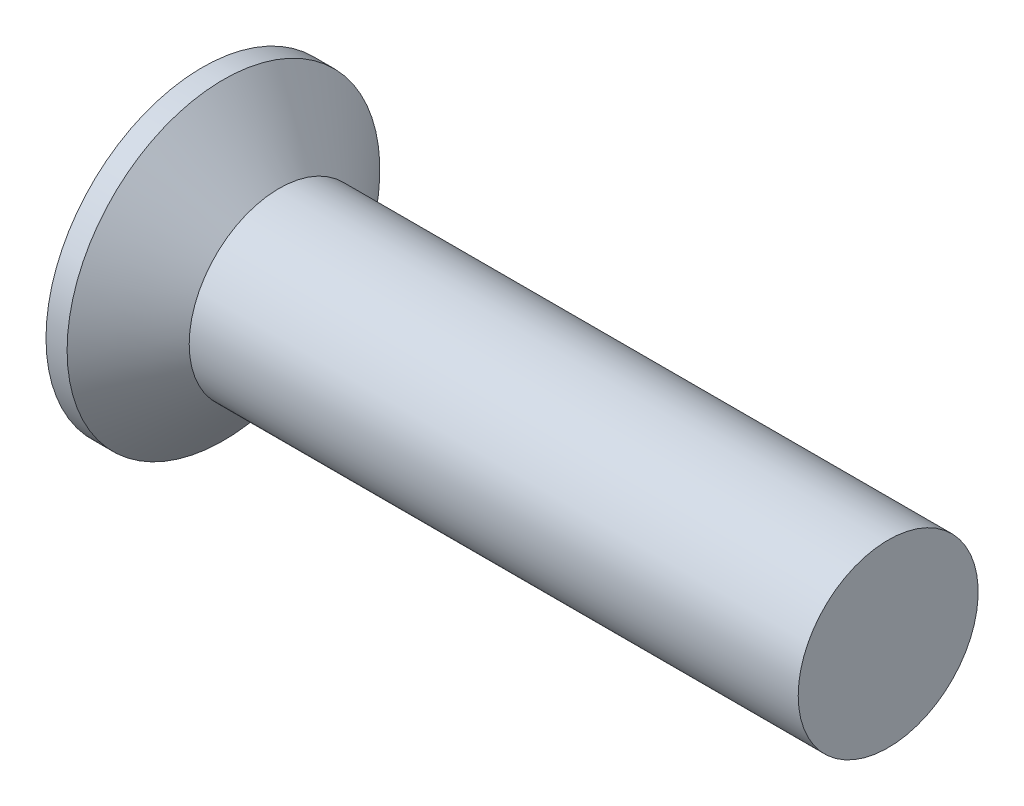
SolidWorks part; units mm, degrees
revolve "Base-Revolve" add sketch "BodySke" angle 360 about L5
sketch "BodySke" plane through (0, 0, 0) normal (0, 0, 1) x (1, 0, 0)
  line L0 (0, 0) -> (0, 3.6195)
  line L1 (0, 3.6195) -> (0.4886, 3.6195)
  line L2 (1.778, 2.0828) -> (15.875, 2.0828)
  line L3 (15.875, 2.0828) -> (15.875, 0)
  line L4 (15.875, 0) -> (0, 0)
  line L5 (-6.35, 0) -> (82.55, 0) construction
  line L6 (1.778, -2.0828) -> (15.875, -2.0828) construction
  line L7 (0.4886, -3.6195) -> (1.778, -2.0828) construction
  line L8 (0.4886, 3.6195) -> (1.778, 2.0828)
  line L9 (0, -3.6195) -> (0.4886, -3.6195) construction
  line L10 (2.5705, 3.6703) -> (2.5705, -5.8547) construction
  line L11 (0, 6.35) -> (0, -3.175) construction
  dimension "Diameter" = 4.1656
  dimension "Length" = 15.875
  dimension "Head_ht" = 1.778
  dimension "Head_dia" = 7.239
  dimension "Head_ang" = 100
  dimension "D6" = 0.4886
  dimension "Advance" = 0.7925
  dimension "Thread_nom" = 15.875
cosmetic thread "ThreadCosmetic" [suppressed] parameters "Thread_length"=13.3045, "Thread_minor"=3.2207
extrude "Slot" [suppressed] cut sketch "Sketch2" against normal blind 0.9144
sketch "Sketch2" plane through (0, 0, 0) normal (-1, 0, 0) x (0, 0, 1)
  line L0 (-3.6195, -0.6858) -> (3.6195, -0.6858)
  line L1 (-3.6195, -0.6858) -> (-3.6195, 0.6858)
  line L2 (3.6195, 0.6858) -> (-3.6195, 0.6858)
  line L3 (3.6195, 0.6858) -> (3.6195, -0.6858)
  dimension "Slot_width" = 1.3716
  dimension "D1" = 0.6858
  dimension "D2" = 7.239
  dimension "D3" = 3.6195
ref_plane "Plane1" through (0, 0, 0) normal (0, 0, 1) x (1, 0, 0)
ref_plane "Plane2" through (0, 0, 0) normal (0, 1, 0) x (1, 0, 0)
ref_plane "Plane3" through (0, 0, 0) normal (1, 0, 0) x (0, 0, -1)
sketch "Sketch3" plane through (0, 0, 0) normal (-1, 0, 0) x (0, 0, 1)
  line L0 (-0.4699, 2.4257) -> (0.4699, 2.4257)
  line L1 (0.4699, 2.4257) -> (0.4699, -2.4257)
  line L2 (0.4699, -2.4257) -> (-0.4699, -2.4257)
  line L3 (-0.4699, -2.4257) -> (-0.4699, 2.4257)
  dimension "Cross_dia" = 4.8514
  dimension "Cross_width" = 0.9398
  dimension "D1" = 2.4257
  dimension "D2" = 0.4699
ref_plane "Plane4" through (3.1496, 0, 0) normal (-1, 0, 0) x (0, 0, 1)
sketch "Sketch4" plane through (3.1496, 0, 0) normal (-1, 0, 0) x (0, 0, 1)
  line L0 (-0.2349, 0.2349) -> (0.2349, 0.235)
  line L3 (0.2349, 0.235) -> (0.235, -0.235)
  line L4 (0.235, -0.235) -> (-0.2349, -0.235)
  line L5 (-0.2349, -0.235) -> (-0.2349, 0.2349)
  dimension "D2" = 0.4699
  dimension "D1" = 0.4699
  dimension "D3" = 0.2349
  dimension "D4" = 0.2349
loft "Cross" cut profiles "Sketch3", "Sketch4"
pattern_circular "CirPattern1" count 2 every 90 about axis through (0, 0, 0) along (1, 0, 0) of "Cross"
sketch "ThdSchSke" plane through (0, 0, 0) normal (0, 0, 1) x (1, 0, 0)
  line L0 (2.5705, -1.6104) -> (2.2397, -2.0828)
  line L1 (2.5705, -1.6104) -> (2.9013, -2.0828)
  line L2 (2.9013, -2.0828) -> (2.9013, -2.6035)
  line L3 (-3.175, 0) -> (5.1513, 0) construction
  line L5 (2.9013, -2.6035) -> (2.2397, -2.6035)
  line L6 (2.2397, -2.6035) -> (2.2397, -2.0828)
  line L7 (0, 3.6195) -> (0, -3.6195) construction
  dimension "Diameter" = 4.1656
  dimension "Thread_minor" = 3.2207
  dimension "Start" = 2.5705
revolve "ThreadSchematic" [suppressed] cut sketch "ThdSchSke" angle 360 about L3
pattern_linear "ThdSchPat" [suppressed]
equation "\"D1@Sketch3\" = \"Cross_dia@Sketch3\" / 2"
equation "\"D2@Sketch3\" = \"Cross_width@Sketch3\" / 2"
equation "\"D1@Sketch4\" = \"Cross_width@Sketch3\" *.5"
equation "\"D2@Sketch4\" = \"D1@Sketch4\""
equation "\"D4@Sketch4\" = \"D2@Sketch4\" / 2"
equation "\"D3@Sketch4\" = \"D1@Sketch4\" / 2"
equation "\"D1@Sketch2\" = \"Slot_width@Sketch2\" / 2"
equation "\"D2@Sketch2\" = \"Head_dia@BodySke\""
equation "\"D3@Sketch2\" = \"D2@Sketch2\" / 2"
equation "\"Thread_length@ThreadCosmetic\" = ((sgn( (\"Length@BodySke\" - \"Advance@BodySke\" - \"Head_ht@BodySke\" ) - \"Thread_nom@BodySke\" )-1)*( (\"Length@BodySke\" - \"Advance@BodySke\" - \"Head_ht@BodySke\" ) - \"Thread_nom@BodySke\" ))/-2+ \"Thread_nom@BodySke\""
equation "\"Thread_minor@ThdSchSke\" = \"Thread_minor@ThreadCosmetic\""
equation "\"Diameter@ThdSchSke\" = \"Diameter@BodySke\""
equation "\"Overcut@ThdSchSke\" = \"Diameter@BodySke\" * 1.25"
equation "\"Start@ThdSchSke\" = 0.000001 + \"Length@BodySke\" - \"Thread_length@ThreadCosmetic\"  '---Countersunk---"
equation "\"Num_threads@ThdSchPat\" = int( \"Thread_length@ThreadCosmetic\" / \"Advance@BodySke\" + 0.999 )  + 1"
equation "\"Advance@ThdSchPat\" = \"Thread_length@ThreadCosmetic\" /  (\"Num_threads@ThdSchPat\" - 1) 'relax it"
